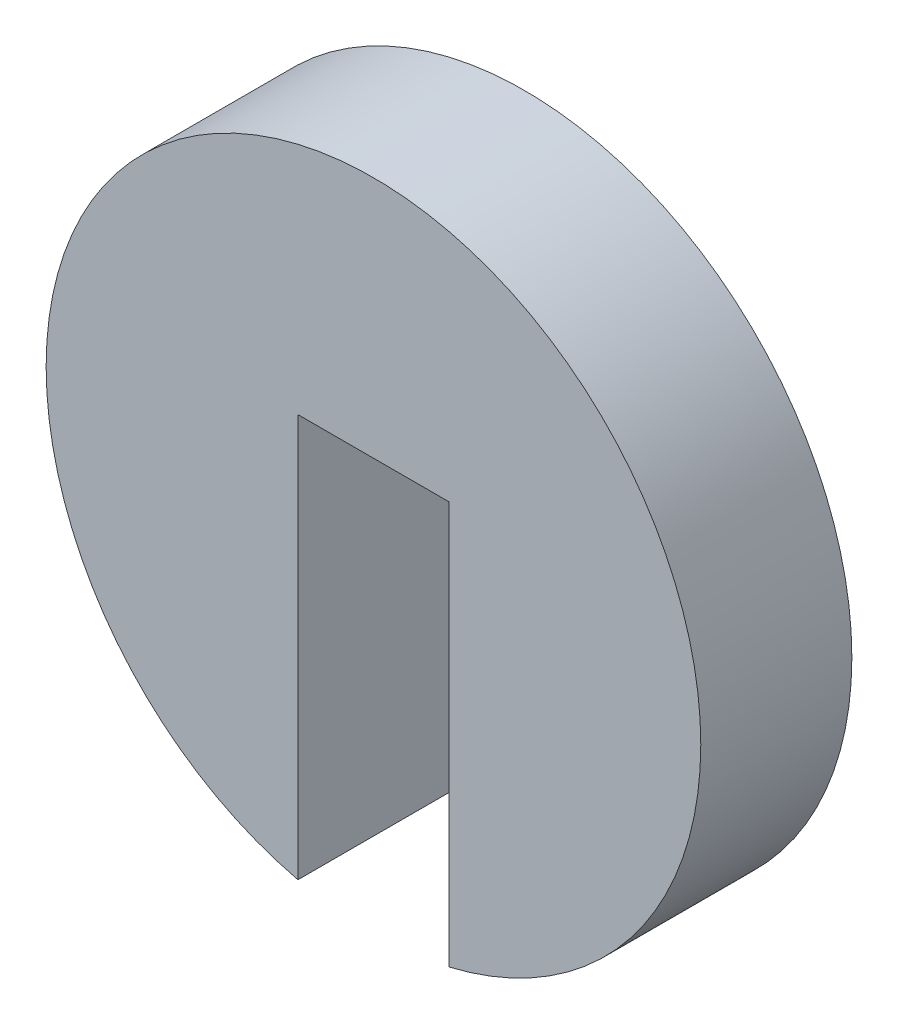
SolidWorks part; units mm, degrees
ref_plane "Front" through (0, 0, 0) normal (0, 0, 1) x (1, 0, 0)
ref_plane "Top" through (0, 0, 0) normal (0, 1, 0) x (1, 0, 0)
ref_plane "Right" through (0, 0, 0) normal (1, 0, 0) x (0, 0, -1)
sketch "Sketch1" plane through (0, 0, 0) normal (0, 0, 1) x (1, 0, 0)
  line L1 (0, 1.6754) -> (1.5, 1.6754)
  line L2 (0, 1.6754) -> (-1.5, 1.6754)
  line L3 (1.5, 1.6754) -> (1.5, -6.3246)
  line L4 (-1.5, 1.6754) -> (-1.5, -6.3246)
  arc A0 (1.5, -6.3246) -> (-1.5, -6.3246) centre (0, 0) ccw
  dimension "D2" = 13
  dimension "D1" = 8
  dimension "D3" = 1.5
  dimension "D4" = 1.5
extrude "Base-Extrude" add sketch "Sketch1" along normal blind 3
